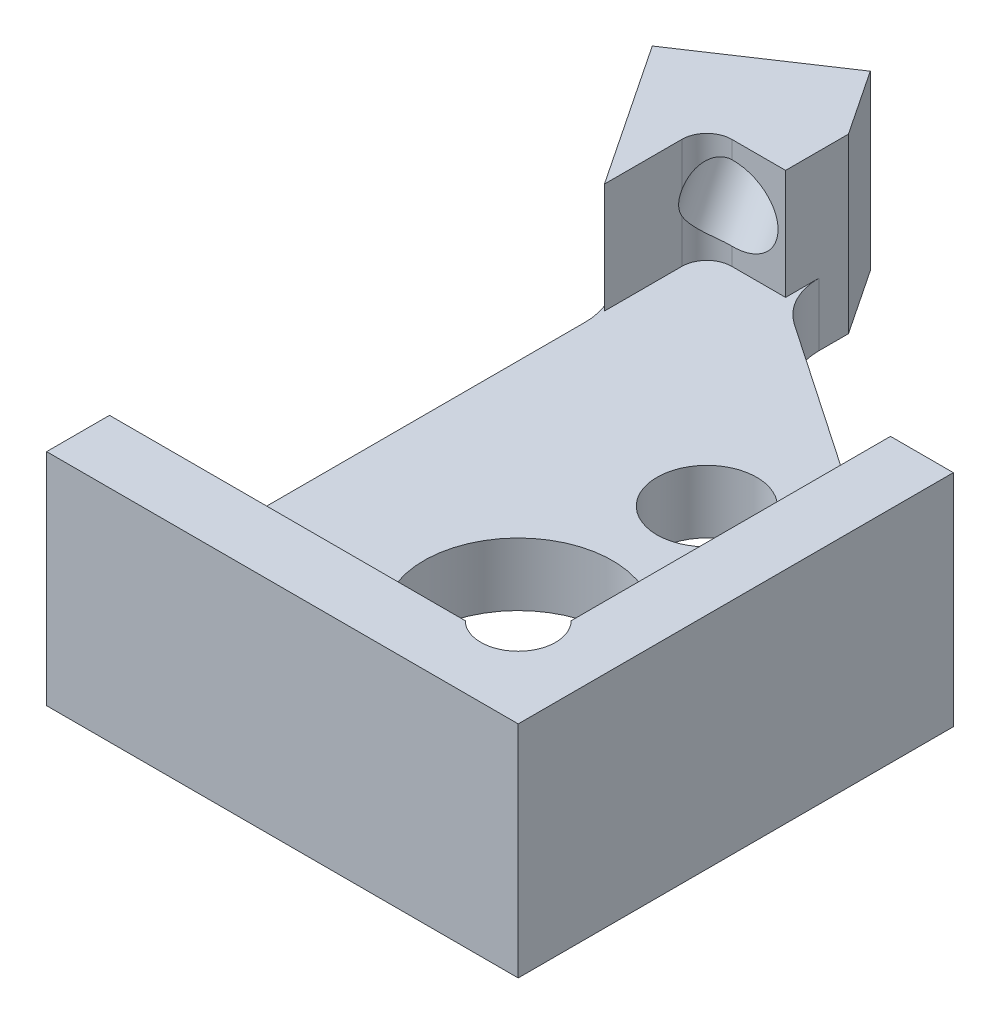
SolidWorks part; units mm, degrees
ref_plane "Front Plane" through (0, 0, 0) normal (0, 0, 1) x (1, 0, 0)
ref_plane "Top Plane" through (0, 0, 0) normal (0, 1, 0) x (1, 0, 0)
ref_plane "Right Plane" through (0, 0, 0) normal (1, 0, 0) x (0, 0, -1)
sketch "Sketch1" plane through (0, 0, 0) normal (0, 1, 0) x (1, 0, 0)
  line L7 (4.25, 5.75) -> (-4.25, 5.75)
  line L8 (4.25, 5.75) -> (4.25, -5.75)
  line L9 (4.25, -5.75) -> (-4.25, -5.75)
  line L10 (-4.25, 5.75) -> (-4.25, -5.75)
  line L11 (4.25, 5.75) -> (-4.25, -5.75) construction
  line L12 (4.25, -5.75) -> (-4.25, 5.75) construction
  point P0 (0, 0)
  point P6 (0, 0)
  dimension "D1" = 8.5
  dimension "D2" = 11.5
extrude "Boss-Extrude1" add sketch "Sketch1" along normal blind 3.5
sketch "Sketch2" plane through (0, 3.5, 0) normal (0, 1, 0) x (1, 0, 0)
  line L0 (-4.25, 5.75) -> (-4.25, -5.75) construction
  line L1 (3.25, 4.75) -> (-3.25, 4.75)
  line L2 (3.25, 4.75) -> (3.25, -4.75)
  line L3 (3.25, -4.75) -> (-3.25, -4.75)
  line L4 (-3.25, 4.75) -> (-3.25, -4.75)
  line L5 (3.25, 4.75) -> (-3.25, -4.75) construction
  line L6 (3.25, -4.75) -> (-3.25, 4.75) construction
  line L7 (4.25, 5.75) -> (-4.25, 5.75) construction
  point P0 (0, 0)
  dimension "D1" = 1
  dimension "D2" = 1
extrude "Cut-Extrude1" cut sketch "Sketch2" against normal offset from surface (2.5 mm away) 1 up to face at (0, 0, 0)
sketch "Sketch3" plane through (0, 1, 0) normal (0, 1, 0) x (1, 0, 0)
  line L0 (-3.25, -4.75) -> (3.25, -4.75) construction
  line L1 (3.25, -4.75) -> (3.25, 4.75) construction
  circle A0 centre (0.25, -1.75) radius 1.5
  dimension "D1" = 3
  dimension "D2" = 3
  dimension "D3" = 3
extrude "Cut-Extrude2" cut sketch "Sketch3" against normal through all
sketch "Sketch6" plane through (0, 3.5, 0) normal (0, 1, 0) x (1, 0, 0)
  line L0 (3.25, -4.75) -> (3.25, 4.75) construction
  line L2 (-3.25, -4.75) -> (3.25, -4.75) construction
  line L3 (3.25, -4.3291) -> (2.8291, -4.3291) construction
  line L4 (2.8291, -4.3291) -> (2.8291, -4.75) construction
  circle A3 centre (2.8291, -4.3291) radius 0.5953
  dimension "D1" = 1.1906
extrude "Cut-Extrude5" cut sketch "Sketch6" against normal up to surface (2.5 mm away) up to face at (0.25, 1, 3.25)
sketch "Sketch7" plane through (0, 1, 0) normal (0, 1, 0) x (1, 0, 0)
  line L0 (2.125, 1.25) -> (-1.625, 1.25) construction
  line L1 (-1.625, 1.25) -> (-1.625, -3.5) construction
  line L2 (-1.625, -3.5) -> (2.125, -3.5) construction
  line L3 (2.125, -3.5) -> (2.125, 1.25) construction
  line L4 (0.25, 1.25) -> (0.25, -1.75) construction
  circle A0 centre (0.25, 1.25) radius 0.7937
  circle A2 centre (-1.625, -3.5) radius 0.7938
  circle A3 centre (2.125, -3.5) radius 0.7938
  circle A4 centre (0.25, -1.75) radius 1.5 construction
  dimension "D1" = 1.5875
  dimension "D2" = 3.75
  dimension "D3" = 3
  dimension "D4" = 1.75
extrude "Cut-Extrude6" cut sketch "Sketch7" against normal through all
sketch "Sketch9" plane through (0, 3.5, 0) normal (0, 1, 0) x (1, 0, 0)
  line L0 (-2.6906, 6.7896) -> (-4.7708, 5.4028)
  line L1 (-3.4116, 4.6422) -> (-4.0015, 4.249)
  line L2 (-3.4116, 4.6422) -> (-2.5113, 5.2425)
  line L3 (-2.6906, 6.7896) -> (-1.9214, 5.6357)
  line L4 (3.25, -4.75) -> (-2.75, 4.25) construction
  line L5 (3.25, -4.75) -> (-2.75, -4.75) construction
  line L6 (-3.25, -4.75) -> (2.4081, -4.75) construction
  line L8 (-2.75, -4.75) -> (-2.75, 4.25) construction
  line L9 (-2.75, 4.25) -> (3.25, 4.25) construction
  line L10 (3.25, -3.9081) -> (3.25, 4.75) construction
  line L11 (3.25, 4.25) -> (3.25, -4.75) construction
  line L12 (-2.75, 3.6498) -> (-1.8497, 4.25) construction
  line L13 (-2.75, 3.6498) -> (-3.4116, 4.6422) construction
  line L14 (-2.2998, 3.9499) -> (-2.9615, 4.9423) construction
  line L15 (-1.9214, 5.6357) -> (-2.5113, 5.2425)
  line L16 (-4.0015, 4.249) -> (-4.7708, 5.4028)
  line L17 (-2.9615, 4.9423) -> (-3.7307, 6.0962) construction
  arc A0 (2.4081, -4.75) -> (3.25, -3.9081) centre (2.8291, -4.3291) ccw construction
  dimension "D1" = 6
  dimension "D2" = 9
  dimension "D3" = 1.082
  dimension "D4" = 2.5
extrude "Boss-Extrude2" add sketch "Sketch9" against normal up to surface (3.5 mm away) up to face at (2.125, 0, 4.2938)
sketch "Sketch14" plane through (0, 3.5, 0) normal (0, 1, 0) x (1, 0, 0)
  line L1 (-6.2326, 2.1835) -> (-0.2674, 2.1835)
  line L2 (-6.2326, 2.1835) -> (-6.2326, 7.3165)
  line L3 (-6.2326, 7.3165) -> (-0.2674, 7.3165)
  line L4 (-0.2674, 2.1835) -> (-0.2674, 7.3165)
  line L5 (-6.2326, 2.1835) -> (-0.2674, 7.3165) construction
  line L6 (-6.2326, 7.3165) -> (-0.2674, 2.1835) construction
  point P0 (-3.25, 4.75)
extrude "Cut-Extrude8" cut sketch "Sketch14" against normal blind 0.75
sketch "Sketch10" plane through (-3.9615, 0, -5.9423) normal (-0.5547, 0, -0.8321) x (-0.8321, 0, 0.5547)
  line L0 (-0.2774, 1) -> (-0.2774, 1.875) construction
  line L1 (-1.5274, 2.75) -> (0.9726, 2.75) construction
  line L2 (-0.2774, 1.875) -> (-0.2774, 2.75) construction
  line L4 (-0.2774, 1) -> (-0.2774, 0) construction
  line L5 (-1.5274, 0) -> (0.9726, 0) construction
  dimension "D1" = 1
hole_wizard "Tap Drill for #0-80 Tap1" positions "Sketch12" profile "Sketch11" hole size "#0-80" standard "ANSI Inch"
sketch "Sketch12" plane through (-3.9615, 0, -5.9423) normal (-0.5547, 0, -0.8321) x (-0.8321, 0, 0.5547)
  point P0 (-0.2774, 1.875)
sketch "Sketch11" plane through (-3.7307, 1.875, -6.0962) normal (0, 1, 0) x (-0.8321, 0, 0.5547)
  line L0 (0, 0) -> (0, 7.4679)
  line L1 (0, 7.4679) -> (0.5956, 7.11)
  line L2 (0.5956, 7.11) -> (0.5956, 0)
  line L5 (0.5956, 0) -> (0, 0)
  line L10 (0, 7.4679) -> (-0.5956, 7.11) construction
  line L11 (0, -6.35) -> (0, 107.95) construction
  dimension "Hole Dia." = 1.1913
  dimension "Hole Depth" = 7.11
  dimension "Drill Angle" = 118
sketch "Sketch13" plane through (0, 3.5, 0) normal (0, 1, 0) x (1, 0, 0)
  line L0 (-1.9976, 5.75) -> (-1.9976, 4.75)
  line L2 (-1.625, -3.5) -> (-3.25, -3.5) construction
  line L3 (3.25, 1.1708) -> (4.25, 1.1708)
  line L4 (4.25, -5.75) -> (4.25, 5.75) construction
  line L5 (4.25, 1.1708) -> (4.25, 5.75)
  line L6 (4.25, 5.75) -> (-1.9976, 5.75)
  line L7 (-4.25, 4.6217) -> (-3.25, 3.1217)
  line L8 (-3.25, 2.1835) -> (-3.25, -4.75) construction
  line L9 (-4.25, 2.1835) -> (-4.25, -5.75) construction
  line L10 (-3.25, 3.1217) -> (-3.25, -5.75)
  line L11 (-4.25, -5.75) -> (4.25, -5.75) construction
  line L12 (-3.25, -5.75) -> (-4.25, -5.75)
  line L13 (-4.25, -5.75) -> (-4.25, 4.6217)
  line L15 (-4.7708, 5.4028) -> (-4.25, 4.6217) construction
  line L17 (-1.9976, 4.75) -> (3.25, 1.1708)
  line L18 (3.25, -3.9081) -> (3.25, 4.75) construction
  line L20 (0.25, 1.25) -> (1.1656, 2.5925) construction
  line L23 (3.25, 4.75) -> (-0.2674, 4.75) construction
extrude "Cut-Extrude7" cut sketch "Sketch13" against normal up to next
fillet "Fillet5" radius 1 3 edges at (-3.25, 0.5, -3.1217) (-1.9976, 0.5, -4.75) (3.25, 0.5, -1.1708)
fillet "Fillet6" radius 0.3969 2 edges at (-3.25, 1.1954, -4.75) (-3.25, 2.5546, -4.75)
